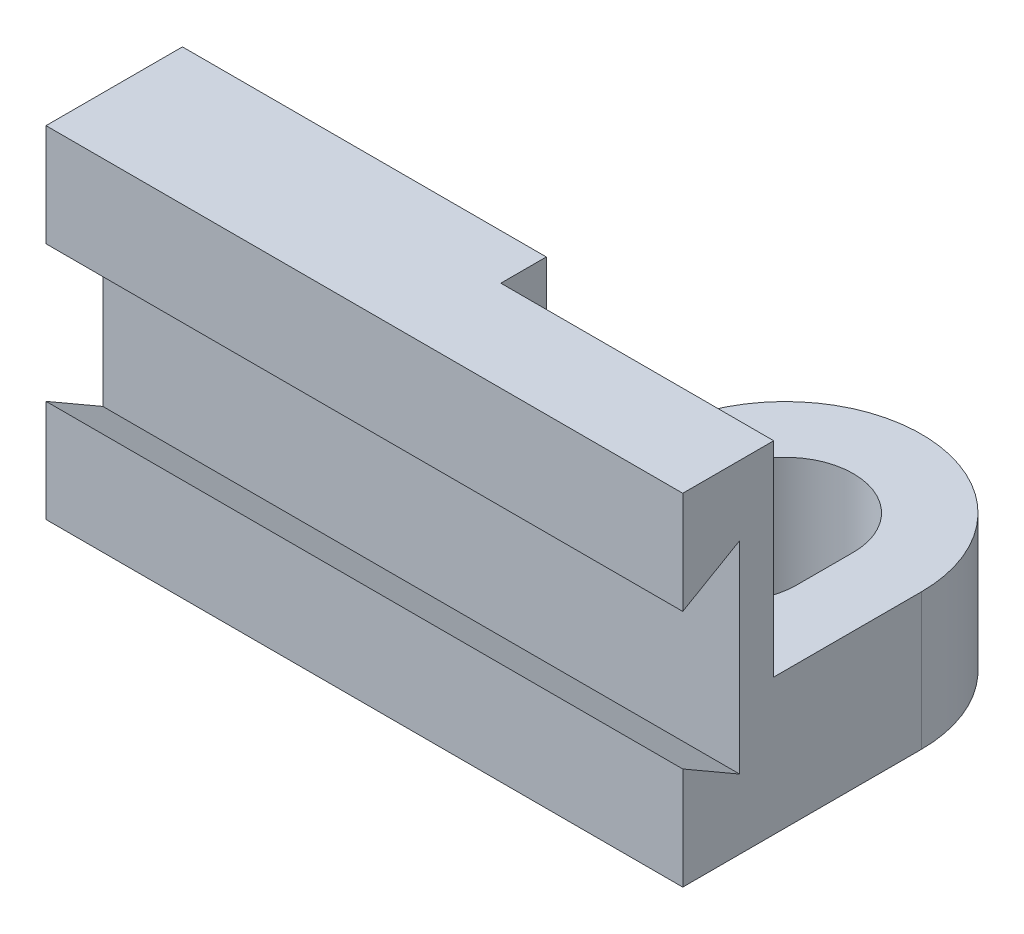
SolidWorks part; units mm, degrees
ref_plane "前视基准面" through (0, 0, 0) normal (0, 0, 1) x (1, 0, 0)
ref_plane "上视基准面" through (0, 0, 0) normal (0, 1, 0) x (1, 0, 0)
ref_plane "右视基准面" through (0, 0, 0) normal (1, 0, 0) x (0, 0, -1)
other "Configuration Table"
sketch "草图1" plane through (0, 0, 0) normal (0, 1, 0) x (1, 0, 0)
  line L0 (0, 0) -> (56, 0)
  line L3 (0, 12) -> (0, 0)
  line L4 (0, 12) -> (32, 12)
  line L5 (32, 12) -> (32, 8)
  line L6 (32, 8) -> (56, 8)
  line L7 (56, 8) -> (56, 0)
  point P6 (0, 0)
  dimension "D1" = 56
  dimension "D2" = 12
  dimension "D3" = 8
  dimension "D4" = 24
extrude "凸台-拉伸1" add sketch "草图1" along normal blind 30
sketch "草图2" plane through (0, 0, 0) normal (-1, 0, 0) x (0, 0, 1)
  line L0 (-5.584, 15.0004) -> (-17.584, 15.0004) construction
  line L1 (0, 15.0007) -> (0, 9.0007)
  line L2 (0, 9.0007) -> (-5, 6.114)
  line L3 (0, 15) -> (0, 21)
  line L4 (0, 30) -> (0, 0) construction
  line L5 (0, 21) -> (-5, 23.8868)
  line L6 (-5, 23.8868) -> (-5, 6.114)
  point P11 (-5, 15.0004)
  line M8 (0, 0) -> (0, 30)
  dimension "D1" = 6
  dimension "D2" = 60
  dimension "D3" = 5
extrude "切除-拉伸1" cut sketch "草图2" against normal through all and the other way through all contours L0 L3 L5 L6 M8 | L1 L0 L6 L2 M8
sketch "草图5" plane through (0, 0, 0) normal (0, -1, 0) x (1, 0, 0)
  line L0 (44, -7.9088) -> (44, -18.5386) construction
  line L1 (50, -16) -> (50, -21)
  line L2 (38, -16) -> (38, -21)
  line L3 (56, -8) -> (32, -8) construction
  line L4 (32, -8) -> (32, -29.8594)
  line L5 (0, -12) -> (0, -20)
  line L6 (0, -20) -> (32, -29.8594)
  line L7 (56, -8) -> (56, -21)
  line L8 (32, -29.8594) -> (40.4666, -32.468)
  circle A0 centre (44, -16) radius 6
  circle A1 centre (44, -21) radius 6
  arc A2 (56, -21) -> (40.4666, -32.468) centre (44, -21) cw
  arc A3 (56, -21) -> (32, -21) centre (44, -21) cw
  point P21 (0, 0)
  point P25 (40.5387, -32.49)
  point P26 (40.523, -32.4851)
  point P27 (32, -29.8592)
  line M11 (0, -12) -> (32, -12)
  line M12 (32, -12) -> (32, -8)
  line M13 (32, -8) -> (56, -8)
  dimension "D3" = 12
  dimension "D1" = 5
  dimension "D2" = 8
  dimension "D4" = 8
  dimension "D5" = 12
  dimension "D6" = 12
extrude "凸台-拉伸2" add sketch "草图5" against normal blind 8 contours L5 L6 L4 M11 | L8 A3 L4 | L0 L4 A3 A1 L2 A0 M13 M12 | L0 A0 L1 A1 A2 L7 M13
sketch "草图6" plane through (0, 8, 0) normal (0, 1, 0) x (1, 0, 0)
  line L0 (44, 8) -> (44, 35.2961) construction
  line L2 (56, 0) -> (56, 8) construction
  line L3 (56, 8) -> (32, 8) construction
  line L4 (32, 21) -> (32, 8)
  line L5 (32, 8) -> (32, 12) construction
  line L6 (32, 12) -> (32, 8) construction
  line L7 (32, 8) -> (56, 8)
  line L8 (56, 8) -> (56, 21)
  line L9 (38, 21) -> (38, 16)
  line L10 (50, 21) -> (50, 16)
  line L11 (50, 16) -> (50, 21) construction
  arc A0 (56, 21) -> (32, 21) centre (44, 21) ccw
  arc A1 (38, 16) -> (50, 16) centre (44, 16) ccw construction
  arc A2 (38, 21) -> (50, 21) centre (44, 21) cw
  arc A3 (38, 16) -> (50, 16) centre (44, 16) ccw
  dimension "D2" = 13
  dimension "D1" = 12
extrude "凸台-拉伸3" add sketch "草图6" along normal blind 4
